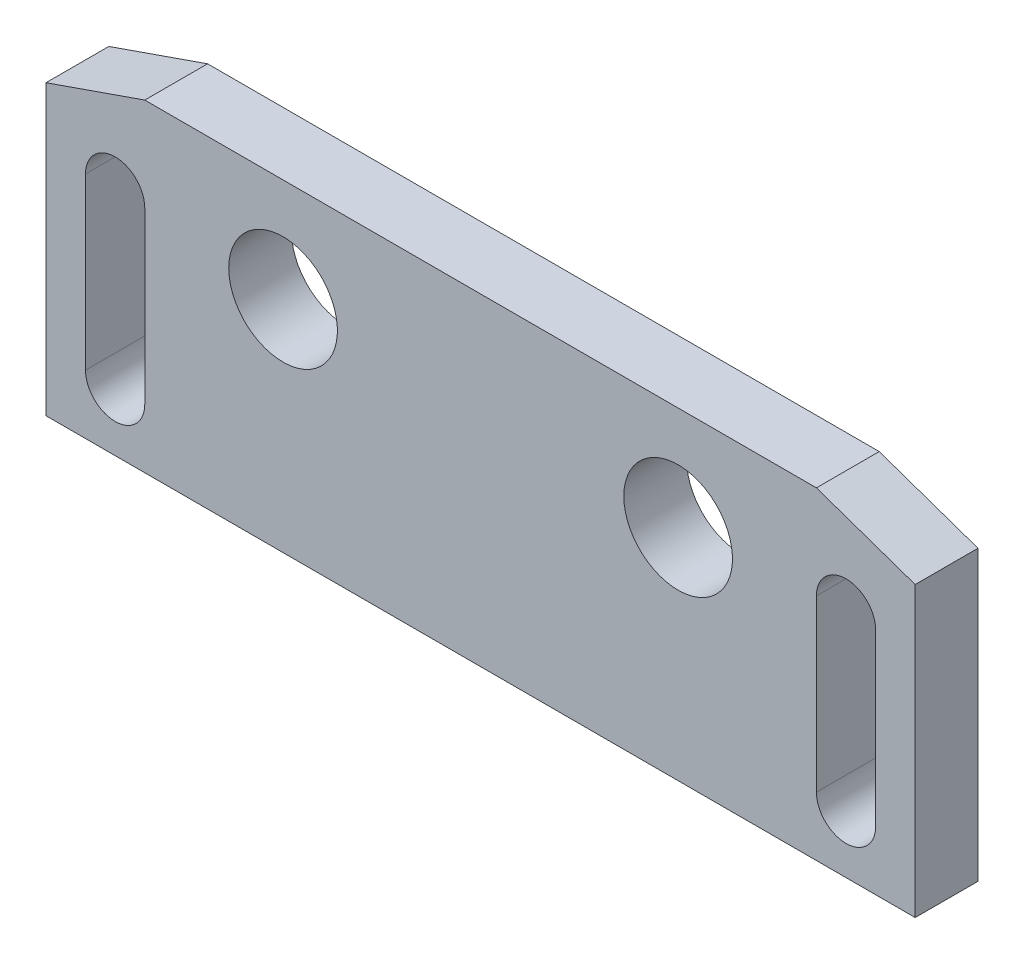
SolidWorks part; units mm, degrees
ref_plane "Front Plane" through (0, 0, 0) normal (0, 0, 1) x (1, 0, 0)
ref_plane "Top Plane" through (0, 0, 0) normal (0, 1, 0) x (1, 0, 0)
ref_plane "Right Plane" through (0, 0, 0) normal (1, 0, 0) x (0, 0, -1)
sketch "Sketch1" plane through (0, 0, 0) normal (0, 0, 1) x (1, 0, 0)
  line L0 (71.5763, -14.4984) -> (87.5763, -14.4984) construction
  line L1 (87.5763, -23.1016) -> (71.5763, -23.1016) construction
  line L2 (-18.5, -14.4984) -> (71.5763, -14.4984) construction
  line L3 (18.5, -23.1016) -> (18.5, -14.4984) construction
  line L4 (20, -23.1016) -> (20, -14.4984)
  line L5 (71.5763, -14.4984) -> (87.5763, -14.4984) construction
  line L6 (87.5763, -23.1016) -> (71.5763, -23.1016) construction
  line L7 (17, -23.1016) -> (17, -14.4984)
  line L8 (-22, -26.1016) -> (22, -26.1016)
  line L9 (-17, -9.7616) -> (17, -9.7616)
  line L10 (22, -11.5) -> (22, -26.1016)
  line L11 (17, -3) -> (-17, -3)
  line L12 (-17, -3) -> (-17, -20)
  line L13 (-17, -20) -> (17, -20)
  line L14 (17, -20) -> (17, -3)
  line L15 (17, -3) -> (-17, -3) construction
  line L16 (-17, -3) -> (-17, -20) construction
  line L17 (-17, -20) -> (17, -20) construction
  line L18 (17, -20) -> (17, -3) construction
  line L19 (17, -9.7616) -> (22, -11.5)
  line L20 (0, -3) -> (0, -20) construction
  line L21 (-17, -11.5) -> (17, -11.5) construction
  line L22 (-18.5, -23.1016) -> (-18.5, -14.4984) construction
  line L23 (-20, -23.1016) -> (-20, -14.4984)
  line L24 (-17, -23.1016) -> (-17, -14.4984)
  line L25 (-18.5, -23.1016) -> (71.5763, -23.1016) construction
  line L26 (-17, -9.7616) -> (-22, -11.5)
  line L27 (-22, -11.5) -> (-22, -26.1016)
  line L28 (-22, -11.5) -> (-17, -11.5) construction
  arc A0 (20, -23.1016) -> (17, -23.1016) centre (18.5, -23.1016) cw
  arc A1 (17, -14.4984) -> (20, -14.4984) centre (18.5, -14.4984) cw
  arc A2 (-20, -23.1016) -> (-17, -23.1016) centre (-18.5, -23.1016) ccw
  arc A3 (-17, -14.4984) -> (-20, -14.4984) centre (-18.5, -14.4984) ccw
  circle A4 centre (10, -15) radius 2.75 construction
  circle A5 centre (-10, -15) radius 2.75 construction
  circle A6 centre (10, -15) radius 2.75
  circle A7 centre (-10, -15) radius 2.75
  point P11 (18.5, -18.8)
  point P17 (0, -11.5)
  point P20 (-18.5, -18.8)
  dimension "D4" = 2
  dimension "D2" = 3
  dimension "D5" = 3
  dimension "D1" = 0
extrude "Boss-Extrude1" add sketch "Sketch1" along normal blind 3.18
